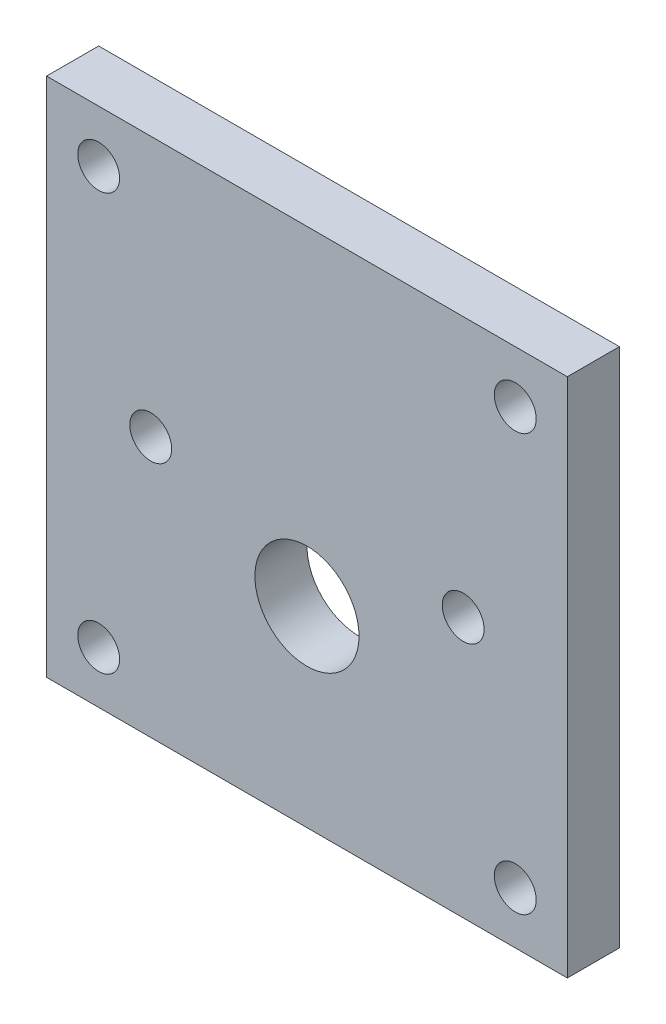
SolidWorks part; units mm, degrees
material "6061 Alloy"
ref_plane "Front Plane" through (0, 0, 0) normal (0, 0, 1) x (1, 0, 0)
ref_plane "Top Plane" through (0, 0, 0) normal (0, 1, 0) x (1, 0, 0)
ref_plane "Right Plane" through (0, 0, 0) normal (1, 0, 0) x (0, 0, -1)
sketch "Sketch1" plane through (0, 0, 0) normal (0, 0, 1) x (1, 0, 0)
  line L1 (-31.75, 31.75) -> (31.75, 31.75)
  line L2 (-31.75, 31.75) -> (-31.75, -31.75)
  line L3 (-31.75, -31.75) -> (31.75, -31.75)
  line L4 (31.75, 31.75) -> (31.75, -31.75)
  line L5 (-31.75, 31.75) -> (31.75, -31.75) construction
  line L6 (-31.75, -31.75) -> (31.75, 31.75) construction
  point P0 (0, 0)
  dimension "D1" = 63.5
  dimension "D2" = 63.5
extrude "Boss-Extrude1" add sketch "Sketch1" along normal blind 6.35
hole_wizard "#10 Clearance Hole3" positions "Sketch3" profile "Sketch4" hole size "#10" standard "ANSI Inch" end condition up to next
sketch "Sketch3" plane through (0, 0, 6.35) normal (0, 0, 1) x (1, 0, 0)
  line L1 (-25.4, 25.4) -> (25.4, 25.4) construction
  line L2 (-25.4, 25.4) -> (-25.4, -25.4) construction
  line L3 (-25.4, -25.4) -> (25.4, -25.4) construction
  line L4 (25.4, 25.4) -> (25.4, -25.4) construction
  line L8 (-25.4, -25.4) -> (25.4, 25.4) construction
  line L10 (31.75, 31.75) -> (-31.75, 31.75) construction
  line L11 (-31.75, 31.75) -> (-31.75, -31.75) construction
  point P0 (-25.4, 25.4)
  point P1 (25.4, -25.4)
  point P268 (-25.4, -25.4)
  point P269 (25.4, 25.4)
  dimension "D1" = 6.35
  dimension "D2" = 6.35
sketch "Sketch4" plane through (-25.4, 25.4, 6.35) normal (1, 0, 0) x (0, -1, 0)
  line L0 (0, 0) -> (0, 6.35)
  line L1 (0, 6.35) -> (2.5527, 6.35)
  line L2 (2.5527, 6.35) -> (2.5527, 0)
  line L5 (2.5527, 0) -> (0, 0)
  line L11 (0, -6.35) -> (0, 107.95) construction
  dimension "Thru Hole Dia." = 5.1054
  dimension "Thru Hole Depth" = 6.35
hole_wizard "#10 Clearance Hole2" positions "Sketch6" profile "Sketch5" hole size "#10" standard "ANSI Inch" end condition up to next
sketch "Sketch6" plane through (0, 0, 6.35) normal (0, 0, 1) x (1, 0, 0)
  line L0 (-19.05, 0) -> (19.05, 0) construction
  point P0 (-19.05, 0)
  point P1 (19.05, 0)
  dimension "D1" = 38.1
sketch "Sketch5" plane through (-19.05, 0, 6.35) normal (1, 0, 0) x (0, -1, 0)
  line L0 (0, 0) -> (0, 6.35)
  line L1 (0, 6.35) -> (2.5527, 6.35)
  line L2 (2.5527, 6.35) -> (2.5527, 0)
  line L5 (2.5527, 0) -> (0, 0)
  line L11 (0, -6.35) -> (0, 107.95) construction
  dimension "Thru Hole Dia." = 5.1054
  dimension "Thru Hole Depth" = 6.35
hole_wizard "Hole1" positions "Sketch8" profile "Sketch7" legacy end condition up to next
sketch "Sketch8" plane through (0, 0, 6.35) normal (0, 0, 1) x (1, 0, 0)
  line L0 (0, 0) -> (0, -8.3566) construction
  point P1 (0, -8.3566)
  dimension "D1" = 8.3566
sketch "Sketch7" plane through (0, -8.3566, 6.35) normal (1, 0, 0) x (0, -1, 0)
  line L0 (0, 0) -> (0, 6.35)
  line L1 (0, 6.35) -> (6.35, 6.35)
  line L2 (6.35, 6.35) -> (6.35, 0)
  line L3 (6.35, 0) -> (0, 0)
  line L4 (0, 110) -> (0, -10) construction
  dimension "Diameter" = 12.7
  dimension "Depth" = 6.35
chamfer "Chamfer1" [suppressed] distance 0.508 angle 45
